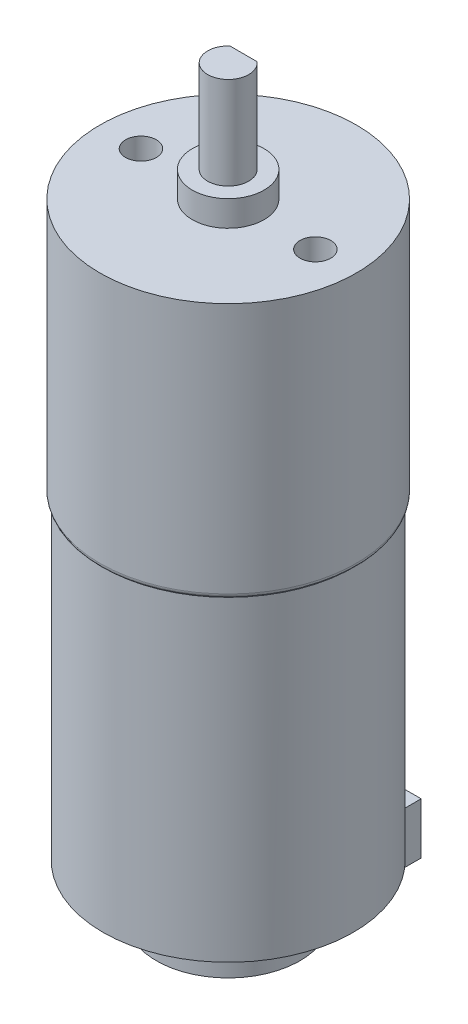
SolidWorks part; units mm, degrees
ref_plane "Front Plane" through (0, 0, 0) normal (0, 0, 1) x (1, 0, 0)
ref_plane "Top Plane" through (0, 0, 0) normal (0, 1, 0) x (1, 0, 0)
ref_plane "Right Plane" through (0, 0, 0) normal (1, 0, 0) x (0, 0, -1)
sketch "Sketch1" plane through (0, 0, 0) normal (0, 1, 0) x (1, 0, 0)
  circle A0 centre (0, 0) radius 12.5
extrude "Boss-Extrude1" add sketch "Sketch1" along normal blind 25 contours A0
fillet "Fillet1" radius 0.5 1 edges at (0, 0, 12.5)
sketch "Sketch3" plane through (0, 0, 0) normal (0, -1, 0) x (1, 0, 0)
  circle A0 centre (0, 0) radius 12.2
extrude "Boss-Extrude2" add sketch "Sketch3" along normal blind 30.8
sketch "Sketch4" plane through (0, 25, 0) normal (0, 1, 0) x (1, 0, 0)
  circle A0 centre (0, 0) radius 3.5
extrude "Boss-Extrude3" add sketch "Sketch4" along normal blind 2.5
sketch "Sketch5" plane through (0, 27.5, 0) normal (0, 1, 0) x (1, 0, 0)
  circle A0 centre (0, 0) radius 2
extrude "Boss-Extrude4" add sketch "Sketch5" along normal blind 9
sketch "Sketch6" plane through (0, 36.5, 0) normal (0, 1, 0) x (1, 0, 0)
  line L0 (0, 0) -> (0, 1.5) construction
  line L1 (1.3229, 1.5) -> (-1.3229, 1.5)
  circle A1 centre (0, 0) radius 2 construction
  arc A2 (-1.3229, 1.5) -> (1.3229, 1.5) centre (0, 0) cw
extrude "Cut-Extrude1" cut sketch "Sketch6" against normal blind 8
sketch "Sketch7" plane through (0, 25, 0) normal (0, 1, 0) x (1, 0, 0)
  line L0 (-8.5, 0) -> (8.5, 0) construction
  circle A0 centre (-8.5, 0) radius 1.5
  circle A1 centre (8.5, 0) radius 1.5
  point P6 (0, 0)
extrude "Cut-Extrude2" cut sketch "Sketch7" against normal blind 5
sketch "Sketch8" plane through (0, -30.8, 0) normal (0, -1, 0) x (1, 0, 0)
  line L0 (0, 0) -> (0, -12.5) construction
  line L2 (-4.2266, -14.5799) -> (4.2266, -14.5799)
  line L3 (-4.2266, -14.5799) -> (-4.2266, -10.4201)
  line L4 (-4.2266, -10.4201) -> (4.2266, -10.4201)
  line L5 (4.2266, -14.5799) -> (4.2266, -10.4201)
  line L6 (-4.2266, -14.5799) -> (4.2266, -10.4201) construction
  line L7 (-4.2266, -10.4201) -> (4.2266, -14.5799) construction
  circle A0 centre (0, 0) radius 7
  circle A1 centre (0, 0) radius 12.5 construction
extrude "Boss-Extrude5" add sketch "Sketch8" along normal blind 5
